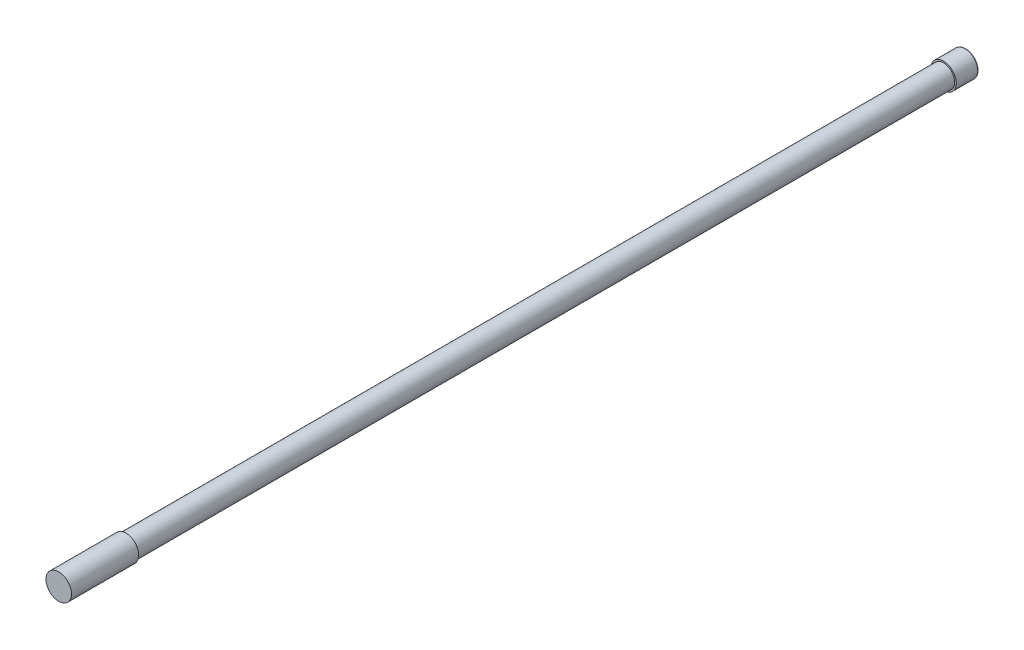
SolidWorks part; units mm, degrees
material "1.4000 (X6Cr13)"
ref_plane "Plan de face" through (0, 0, 0) normal (0, 0, 1) x (1, 0, 0)
ref_plane "Plan de dessus" through (0, 0, 0) normal (0, 1, 0) x (1, 0, 0)
ref_plane "Plan de droite" through (0, 0, 0) normal (1, 0, 0) x (0, 0, -1)
sketch "Esquisse1" plane through (0, 0, 0) normal (0, 0, 1) x (1, 0, 0)
  circle A0 centre (0, 0) radius 11.4
extrude "Boss.-Extru.1" add sketch "Esquisse1" along normal blind 60
sketch "Esquisse2" plane through (0, 0, 0) normal (0, 0, -1) x (-1, 0, 0)
  circle A0 centre (0, 0) radius 10
extrude "Boss.-Extru.2" add sketch "Esquisse2" along normal blind 750
sketch "Esquisse3" plane through (0, 0, -750) normal (0, 0, -1) x (-1, 0, 0)
  circle A0 centre (0, 0) radius 11.4
extrude "Boss.-Extru.3" add sketch "Esquisse3" against normal blind 20
fillet "Congé1" radius 1 1 edges at (-11.4, 0, -750)
